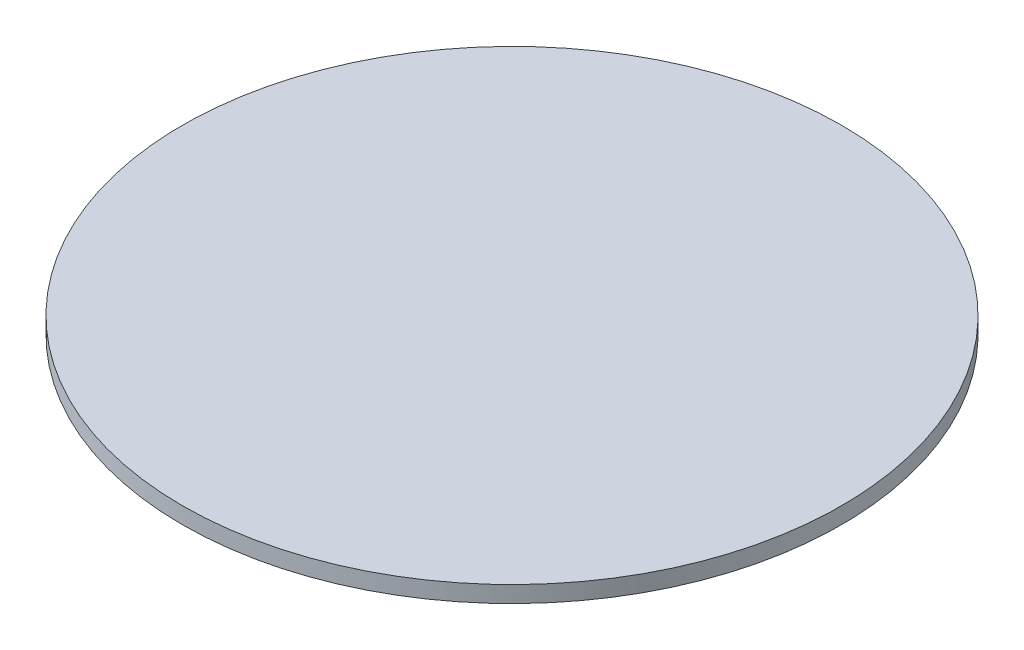
SolidWorks part; units mm, degrees
ref_plane "Alzado" through (0, 0, 0) normal (0, 0, 1) x (1, 0, 0)
ref_plane "Planta" through (0, 0, 0) normal (0, 1, 0) x (1, 0, 0)
ref_plane "Vista lateral" through (0, 0, 0) normal (1, 0, 0) x (0, 0, -1)
sketch "Croquis1" plane through (0, 0, 0) normal (0, 1, 0) x (1, 0, 0)
  circle A0 centre (0, 0) radius 60
  dimension "D1" = 120
extrude "Saliente-Extruir1" add sketch "Croquis1" along normal blind 3
